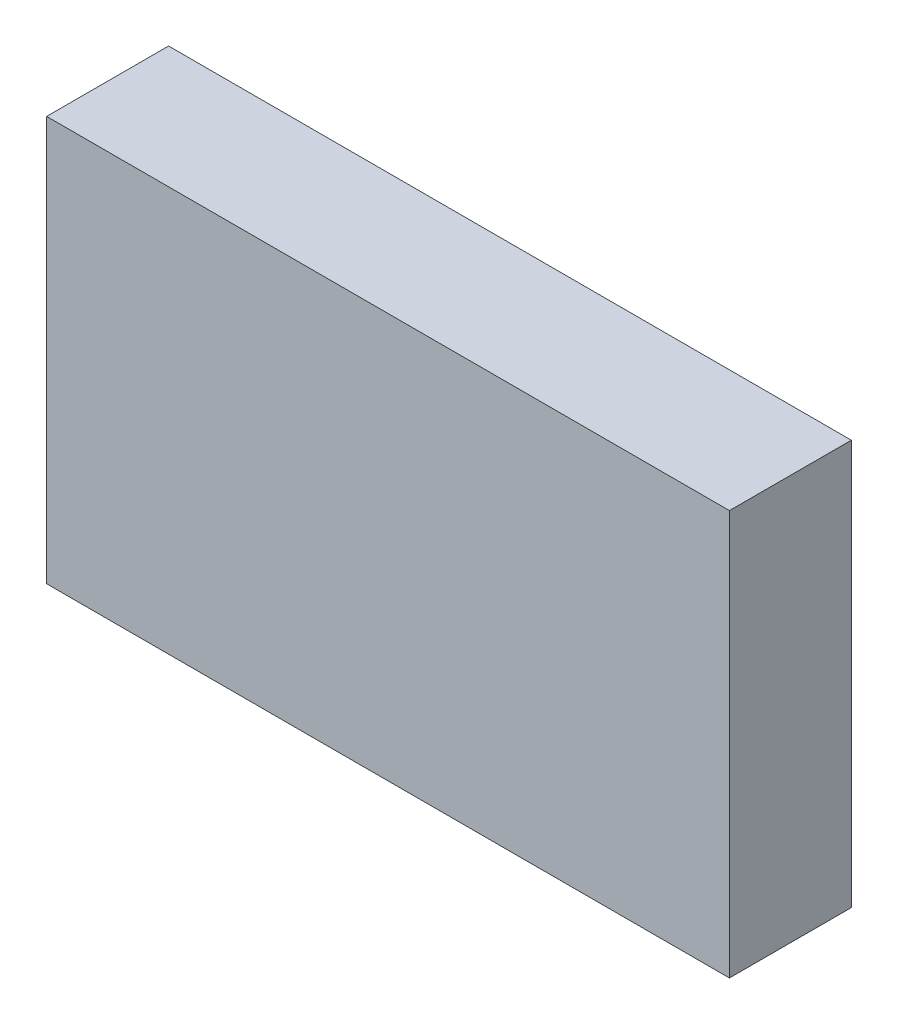
SolidWorks part; units mm, degrees
ref_plane "前视基准面" through (0, 0, 0) normal (0, 0, 1) x (1, 0, 0)
ref_plane "上视基准面" through (0, 0, 0) normal (0, 1, 0) x (1, 0, 0)
ref_plane "右视基准面" through (0, 0, 0) normal (1, 0, 0) x (0, 0, -1)
sketch "草图1" plane through (0, 0, 0) normal (0, 0, 1) x (1, 0, 0)
  line L1 (70, -41.5) -> (-70, -41.5)
  line L2 (70, -41.5) -> (70, 41.5)
  line L3 (70, 41.5) -> (-70, 41.5)
  line L4 (-70, -41.5) -> (-70, 41.5)
  line L5 (70, -41.5) -> (-70, 41.5) construction
  line L6 (70, 41.5) -> (-70, -41.5) construction
  point P0 (0, 0)
  dimension "D1" = 140
  dimension "D2" = 83
extrude "凸台-拉伸1" add sketch "草图1" along normal blind 25
